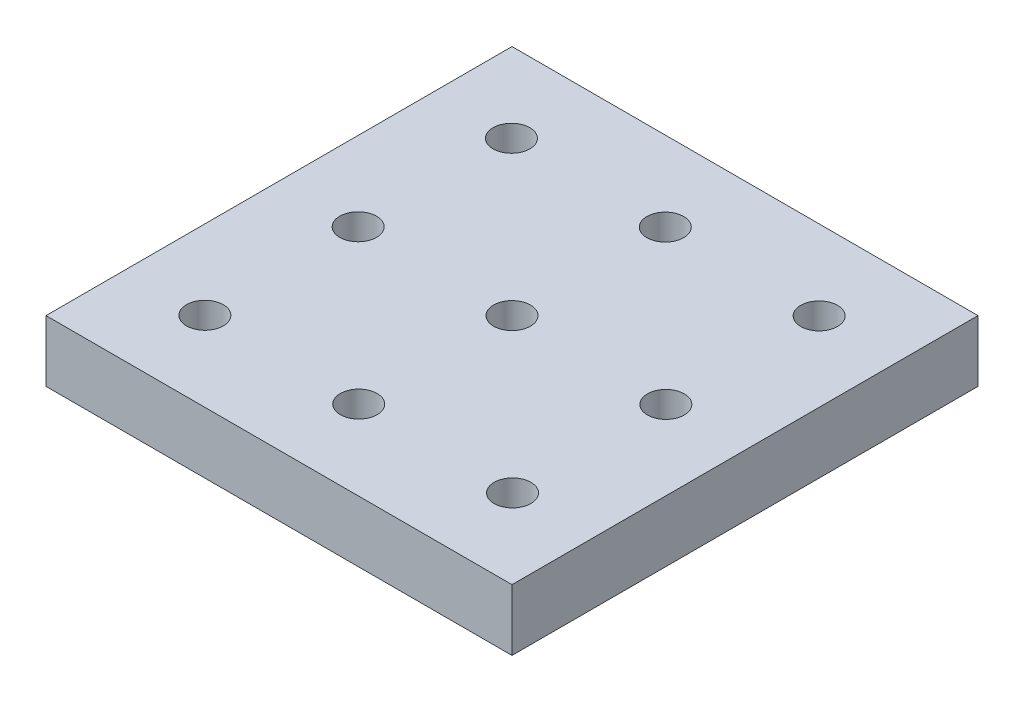
SolidWorks part; units mm, degrees
ref_plane "Front Plane" through (0, 0, 0) normal (0, 0, 1) x (1, 0, 0)
ref_plane "Top Plane" through (0, 0, 0) normal (0, 1, 0) x (1, 0, 0)
ref_plane "Right Plane" through (0, 0, 0) normal (1, 0, 0) x (0, 0, -1)
sketch "Sketch1" plane through (0, 0, 0) normal (0, 1, 0) x (1, 0, 0)
  line L1 (-121.8597, 43.7102) -> (-121.8597, 119.7102)
  line L2 (-121.8597, 119.7102) -> (-197.8597, 119.7102)
  line L3 (-197.8597, 119.7102) -> (-197.8597, 43.7102)
  line L4 (-197.8597, 43.7102) -> (-121.8597, 43.7102)
  circle A0 centre (-159.8597, 81.7102) radius 3
  circle A1 centre (-134.7695, 81.7102) radius 3
  circle A2 centre (-184.9499, 81.7102) radius 3
  circle A3 centre (-184.9499, 106.7102) radius 3
  circle A4 centre (-159.8597, 106.7102) radius 3
  circle A5 centre (-134.7695, 106.7102) radius 3
  circle A6 centre (-134.7695, 56.7102) radius 3
  circle A7 centre (-159.8597, 56.7102) radius 3
  circle A8 centre (-184.9499, 56.7102) radius 3
extrude "Boss-Extrude1" add sketch "Sketch1" along normal blind 10
sketch "Sketch2" plane through (0, 0, 0) normal (0, -1, 0) x (1, 0, 0)
  line L0 (-197.8597, -43.7102) -> (-121.8597, -43.7102)
  line L1 (-197.8597, -119.7102) -> (-121.8597, -119.7102)
  line L2 (-121.8597, -119.7102) -> (-197.8597, -119.7102) construction
  point P9 (-185.8597, -43.7102)
  point P10 (-209.8597, -43.7102)
  dimension "D1" = 12
  dimension "D2" = 12
sketch "Sketch3" plane through (0, 10, 0) normal (0, 1, 0) x (1, 0, 0)
  line L0 (-192.8597, 119.7102) -> (-192.8597, 43.7102)
  line L1 (-197.8597, 119.7102) -> (-121.8597, 119.7102) construction
  line L2 (-197.8597, 43.7102) -> (-121.8597, 43.7102) construction
  line L3 (-192.8597, 81.7102) -> (-187.8597, 81.7102)
  line L4 (-197.8597, 119.7102) -> (-197.8597, 43.7102) construction
  line L5 (-197.8597, 119.7102) -> (-197.8597, 43.7102)
  line L6 (-197.8597, 43.7102) -> (-121.8597, 43.7102)
  line L7 (-121.8597, 43.7102) -> (-121.8597, 119.7102)
  line L8 (-121.8597, 119.7102) -> (-197.8597, 119.7102)
  line L9 (-187.8597, 116.2102) -> (-121.8597, 116.2102)
  line L10 (-187.8597, 116.2102) -> (-187.8597, 111.2102) construction
  line L11 (-187.8597, 44.2102) -> (-187.8597, 119.2102) construction
  line L12 (-187.8597, 111.2102) -> (-121.8597, 111.2102)
  line L13 (-121.8597, 43.7102) -> (-121.8597, 119.7102) construction
  line L14 (-187.8597, 93.2102) -> (-121.8597, 93.2102)
  line L15 (-187.8597, 88.2102) -> (-121.8597, 88.2102)
  line L16 (-187.8597, 119.2102) -> (-187.8597, 44.2102) construction
  line L17 (-187.8597, 47.2102) -> (-121.8597, 47.2102)
  line L18 (-187.8597, 52.2102) -> (-121.8597, 52.2102)
  line L19 (-187.8597, 70.2102) -> (-121.8597, 70.2102)
  line L20 (-187.8597, 75.2102) -> (-121.8597, 75.2102)
  line L21 (-177.8597, 116.2102) -> (-177.8597, 47.2102)
  line L22 (-167.8597, 116.2102) -> (-167.8597, 47.2102)
  line L23 (-154.8597, 116.2102) -> (-154.8597, 47.2102)
  line L24 (-144.8597, 116.2102) -> (-144.8597, 47.2102)
  line L25 (-148.8597, 119.7102) -> (-148.8597, 47.2102)
  line L26 (-187.8597, 119.2102) -> (-187.8597, 47.2102)
  line L27 (-187.8597, 109.2102) -> (-180.0496, 109.2102)
  line L28 (-187.8597, 94.2102) -> (-182.9706, 94.2102)
  line L29 (-187.8597, 69.2102) -> (-180.7693, 69.2102)
  line L30 (-187.8597, 54.2102) -> (-180.0496, 54.2102)
  circle A0 centre (-134.7695, 106.7102) radius 3 construction
  circle A1 centre (-159.8597, 106.7102) radius 3 construction
  circle A2 centre (-184.9499, 106.7102) radius 3 construction
  circle A3 centre (-184.9499, 81.7102) radius 3 construction
  circle A4 centre (-159.8597, 81.7102) radius 3 construction
  circle A5 centre (-134.7695, 81.7102) radius 3 construction
  circle A6 centre (-134.7695, 56.7102) radius 3 construction
  circle A7 centre (-159.8597, 56.7102) radius 3 construction
  circle A8 centre (-184.9499, 56.7102) radius 3 construction
  circle A9 centre (-134.7695, 106.7102) radius 3
  circle A10 centre (-159.8597, 106.7102) radius 3
  circle A11 centre (-184.9499, 106.7102) radius 3
  circle A12 centre (-184.9499, 81.7102) radius 3
  circle A13 centre (-159.8597, 81.7102) radius 3
  circle A14 centre (-134.7695, 81.7102) radius 3
  circle A15 centre (-134.7695, 56.7102) radius 3
  circle A16 centre (-159.8597, 56.7102) radius 3
  circle A17 centre (-184.9499, 56.7102) radius 3
  dimension "D1" = 5
  dimension "D2" = 5
  dimension "D3" = 39
  dimension "D4" = 10
  dimension "D5" = 10
  dimension "D6" = 10
